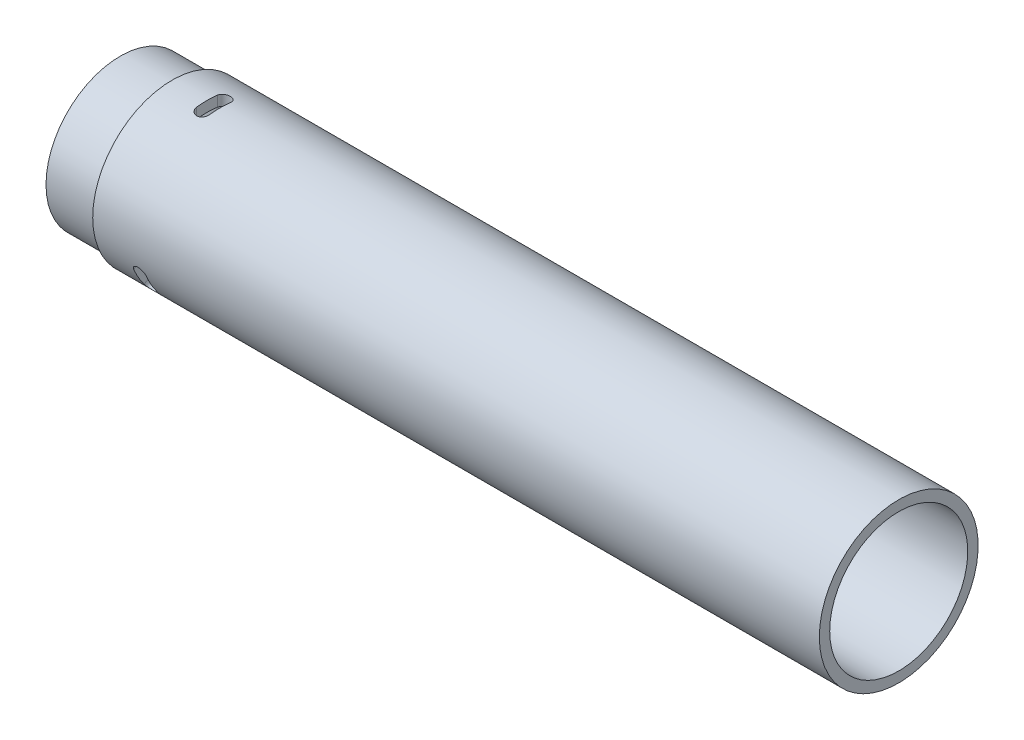
SolidWorks part; units mm, degrees
material "Copper"
ref_plane "Front Plane" through (0, 0, 0) normal (0, 0, 1) x (1, 0, 0)
ref_plane "Top Plane" through (0, 0, 0) normal (0, 1, 0) x (1, 0, 0)
ref_plane "Right Plane" through (0, 0, 0) normal (1, 0, 0) x (0, 0, -1)
sketch "Sketch1" plane through (0, 0, 0) normal (0, 0, 1) x (1, 0, 0)
  line L0 (0, 0) -> (22.4873, 0)
  line L5 (15.2485, 19.431) -> (193.0485, 19.431)
  line L6 (2.5485, 16.891) -> (193.0485, 16.891)
  line L7 (193.0485, 19.431) -> (193.0485, 16.891)
  line L11 (15.2485, 19.431) -> (15.2485, 18.161)
  line L12 (15.2485, 18.161) -> (2.5485, 18.161)
  line L13 (2.5485, 18.161) -> (2.5485, 16.891)
  dimension "D1" = 16.891
  dimension "D2" = 177.8
  dimension "D3" = 12.7
  dimension "D4" = 2.54
revolve "Revolve1" add sketch "Sketch1" angle 360 about L0
ref_plane "Plane1" through (0, 19.431, 0) normal (0, 1, 0) x (1, 0, 0)
sketch "Sketch2" plane through (0, 19.431, 0) normal (0, 1, 0) x (1, 0, 0)
  line L0 (25.4, 0) -> (25.4, 2.54)
  line L1 (15.2485, 0) -> (193.0485, 0) construction
  line L2 (25.4, 0) -> (25.4, -2.54)
  line L3 (25.4, 2.54) -> (25.4, -2.54) construction
  line L4 (26.9875, 2.54) -> (26.9875, -2.54)
  line L5 (23.8125, 2.54) -> (23.8125, -2.54)
  arc A1 (26.9875, 2.54) -> (23.8125, 2.54) centre (25.4, 2.54) ccw
  arc A2 (23.8125, -2.54) -> (26.9875, -2.54) centre (25.4, -2.54) ccw
  point P4 (25.4, 0)
extrude "Cut-Extrude1" cut sketch "Sketch2" against normal blind 7.62 contours L4 A2 L5 A1
pattern_circular "CirPattern1" count 3 every 120 about axis through (0, 0, 0) along (-1, 0, 0) of "Cut-Extrude1"
